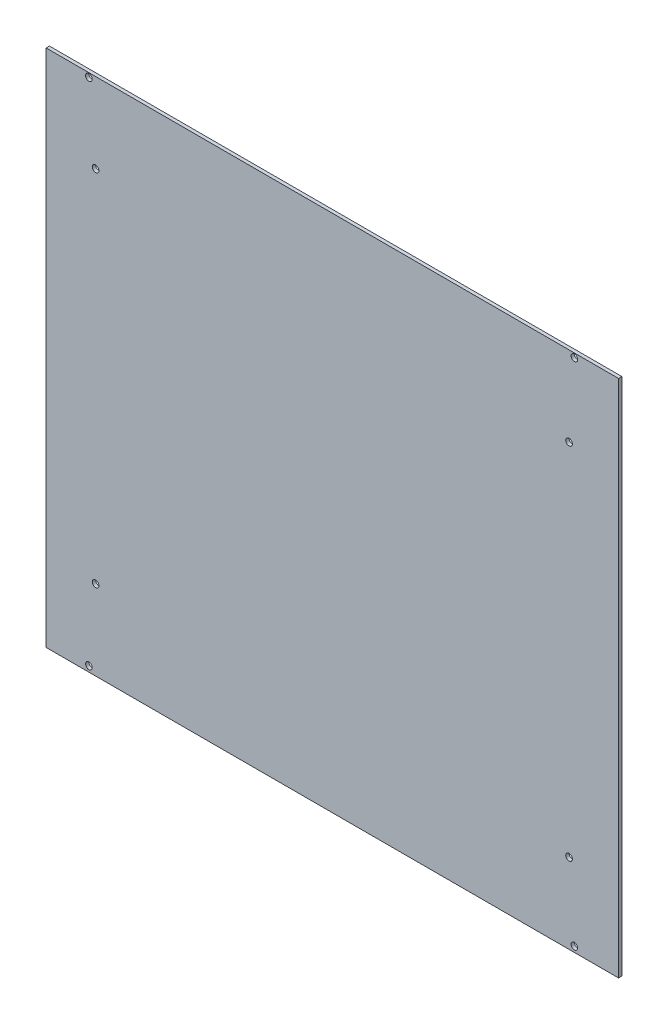
SolidWorks part; units mm, degrees
ref_plane "Front Plane" through (0, 0, 0) normal (0, 0, 1) x (1, 0, 0)
ref_plane "Top Plane" through (0, 0, 0) normal (0, 1, 0) x (1, 0, 0)
ref_plane "Right Plane" through (0, 0, 0) normal (1, 0, 0) x (0, 0, -1)
sketch "Sketch1" plane through (0, 0, 0) normal (0, 0, 1) x (1, 0, 0)
  line L1 (-273.05, -247.65) -> (273.05, -247.65)
  line L2 (-273.05, -247.65) -> (-273.05, 247.65)
  line L3 (-273.05, 247.65) -> (273.05, 247.65)
  line L4 (273.05, -247.65) -> (273.05, 247.65)
  line L5 (-273.05, -247.65) -> (273.05, 247.65) construction
  line L6 (-273.05, 247.65) -> (273.05, -247.65) construction
  point P0 (0, 0)
  dimension "D1" = 546.1
  dimension "D2" = 495.3
extrude "Boss-Extrude1" add sketch "Sketch1" along normal blind 3.175 contours L2 L1 L4 L3
sketch "Sketch3" plane through (0, 0, 3.175) normal (0, 0, 1) x (1, 0, 0)
  line L0 (0, 0) -> (0, 77.5284)
  line L3 (0, 0) -> (-70.16, 0)
  circle A0 centre (-225.806, 171.45) radius 3.175
  circle A1 centre (225.806, 171.45) radius 3.175
  circle A2 centre (225.806, -171.45) radius 3.175
  circle A3 centre (-225.806, -171.45) radius 3.175
extrude "Cut-Extrude2" cut sketch "Sketch3" against normal blind 3.175 contours A0 | A1 | A3 | A2
sketch "Sketch6" plane through (0, 0, 0) normal (0, 0, -1) x (-1, 0, 0)
  circle A0 centre (-230.8948, -242.4106) radius 3.175
  circle A1 centre (-230.8948, 243.7246) radius 3.175
  circle A2 centre (232.2089, -242.4106) radius 3.175
  circle A3 centre (232.2089, 243.7246) radius 3.175
extrude "Cut-Extrude3" cut sketch "Sketch6" against normal blind 6.35
